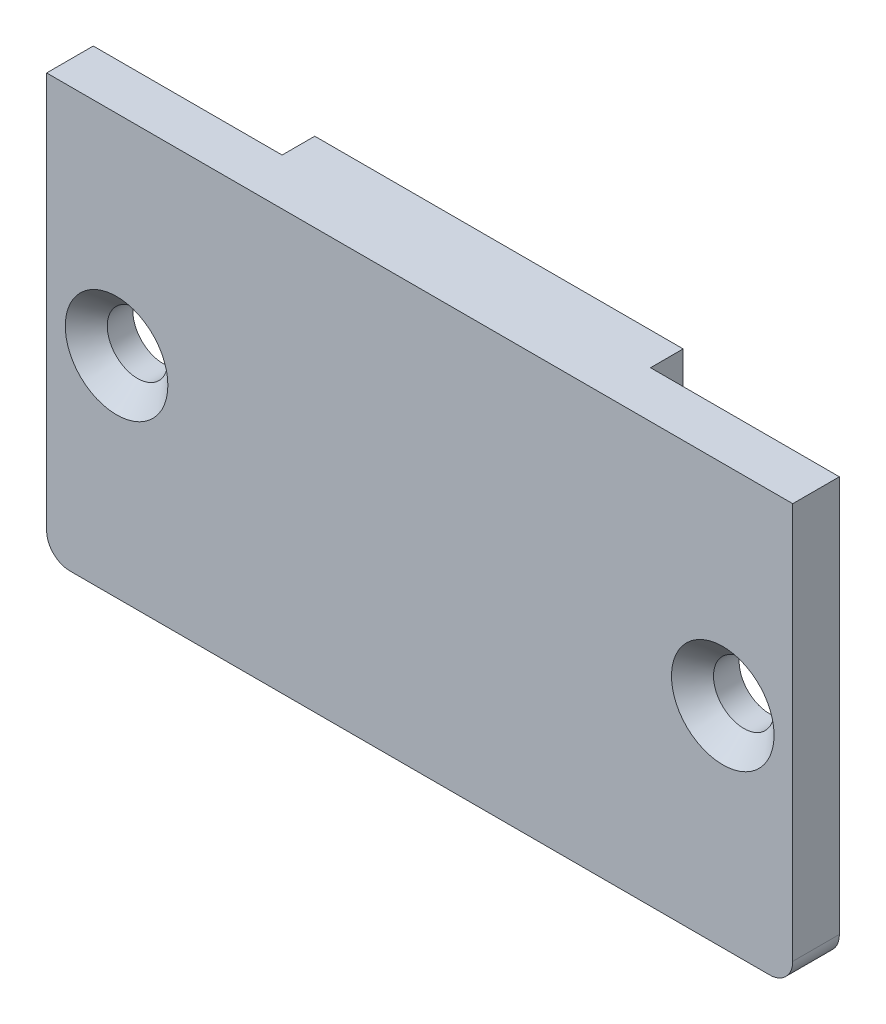
SolidWorks part; units mm, degrees
ref_plane "Plan de face" through (0, 0, 0) normal (0, 0, 1) x (1, 0, 0)
ref_plane "Plan de dessus" through (0, 0, 0) normal (0, 1, 0) x (1, 0, 0)
ref_plane "Plan de droite" through (0, 0, 0) normal (1, 0, 0) x (0, 0, -1)
sketch "Esquisse1" plane through (0, 0, 0) normal (0, 0, 1) x (1, 0, 0)
  line L1 (-16, -9) -> (16, -9)
  line L2 (-16, -9) -> (-16, 9)
  line L3 (-16, 9) -> (16, 9)
  line L4 (16, -9) -> (16, 9)
  line L5 (-16, -9) -> (16, 9) construction
  line L6 (-16, 9) -> (16, -9) construction
  point P0 (0, 0)
  dimension "D1" = 32
  dimension "D2" = 18
extrude "Boss.-Extru.1" add sketch "Esquisse1" along normal blind 2
sketch "Esquisse2" plane through (0, 0, 0) normal (0, 0, -1) x (-1, 0, 0)
  line L0 (-16, 9) -> (16, 9) construction
  line L1 (-9.5, -7) -> (9.5, -7)
  line L2 (-9.5, -7) -> (-9.5, 7)
  line L3 (-9.5, 7) -> (9.5, 7)
  line L4 (9.5, -7) -> (9.5, 7)
  line L5 (-9.5, -7) -> (9.5, 7) construction
  line L6 (-9.5, 7) -> (9.5, -7) construction
  point P0 (0, 0)
  dimension "D1" = 2
  dimension "D2" = 19
extrude "Boss.-Extru.2" add sketch "Esquisse2" along normal blind 1.4
fillet "Congé1" [suppressed] radius 1
fillet "Congé2" [suppressed] radius 0.6
fillet "Congé3" [suppressed] radius 1
hole_wizard "Fraisage pour vis à tête fraisée M21" positions "Esquisse4" profile "Esquisse5" countersink size "M2" standard "ISO" end condition through all
sketch "Esquisse4" plane through (0, 0, 2) normal (0, 0, 1) x (1, 0, 0)
  line L0 (-16, 0) -> (16, 0) construction
  point P0 (-13, 0)
  dimension "D1" = 13
sketch "Esquisse5" plane through (-13, 0, 2) normal (1, 0, 0) x (0, -1, 0)
  line L0 (0, 0) -> (0, 3.4)
  line L1 (0, 3.4) -> (1.3, 3.4)
  line L2 (1.3, 3.4) -> (1.3, 0.9)
  line L3 (1.3, 0.9) -> (2.2, 0)
  line L5 (2.2, 0) -> (0, 0)
  line L6 (-1.3, 0.9) -> (-2.2, 0) construction
  line L11 (0, -6.35) -> (0, 107.95) construction
  dimension "Diamètre du perçage jusqu'au prochain" = 2.6
  dimension "Profondeur du perçage jusqu'au prochain" = 3.4
  dimension "Diamètre du fraisage entrant" = 4.4
  dimension "Angle du fraisage entrant" = 90
mirror "Symétrie1" about plane through (0, 0, 0) normal (1, 0, 0) of "Fraisage pour vis à tête fraisée M21"
sketch "Esquisse6" plane through (0, 0, 0) normal (0, 0, -1) x (-1, 0, 0)
  line L0 (0, 0) -> (0, 12.4758) construction
  line L1 (9.5, 7) -> (-9.5, 7) construction
  line L2 (-7.9, 9) -> (7.9, 9)
  line L3 (-7.9, 9) -> (-7.9, 7)
  line L4 (-7.9, 7) -> (7.9, 7)
  line L5 (7.9, 9) -> (7.9, 7)
  line L6 (-7.9, 9) -> (7.9, 7) construction
  line L7 (-7.9, 7) -> (7.9, 9) construction
  line L8 (-16, 9) -> (16, 9) construction
  point P3 (0, 8)
  dimension "D1" = 15.8
extrude "Boss.-Extru.3" add sketch "Esquisse6" along normal up to surface (1.4 mm away) up to face at (0, 0, -1.4)
sketch "Esquisse7" plane through (0, 0, 2) normal (0, 0, 1) x (1, 0, 0)
  line L0 (7.9, 7) -> (9.5, 7) construction
  line L5 (0, 9) -> (0, 3.4178) construction
  line L6 (9.6, 7) -> (-9.6, 7)
  line L7 (9.6, 7) -> (9.6, 5.8)
  line L8 (9.6, 5.8) -> (-9.6, 5.8)
  line L9 (-9.6, 7) -> (-9.6, 5.8)
  line L10 (-7.9, 9) -> (7.9, 9) construction
  dimension "D1" = 19.2
  dimension "D2" = 1.2
extrude "Boss.-Extru.4" add sketch "Esquisse7" against normal up to surface (3.4 mm away) up to face at (0, 4, -1.4)
fillet "Congé7" radius 1 2 edges at (16, -9, 1) (-16, -9, 1)
